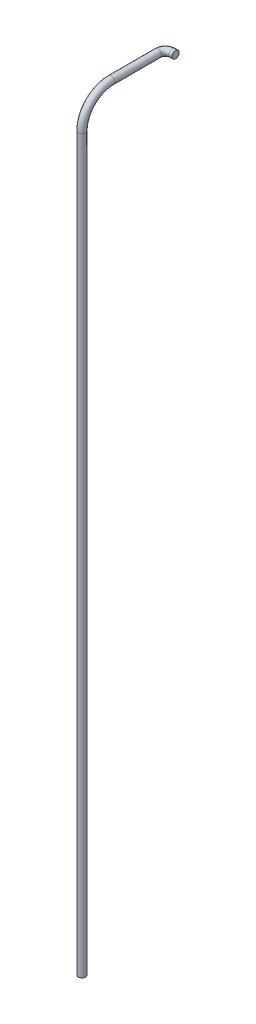
SolidWorks part; units mm, degrees
material "PVC Rígido"
ref_plane "Plano frontal" through (0, 0, 0) normal (0, 0, 1) x (1, 0, 0)
ref_plane "Plano superior" through (0, 0, 0) normal (0, 1, 0) x (1, 0, 0)
ref_plane "Plano direito" through (0, 0, 0) normal (1, 0, 0) x (0, 0, -1)
sketch "Esboço1" plane through (0, 0, 0) normal (1, 0, 0) x (0, 0, -1)
  line L0 (0, 0) -> (-30, 0)
  line L1 (-50, -20) -> (-50, -520)
  arc A1 (-30, 0) -> (-50, -20) centre (-30, -20) ccw
  point P7 (-50, -1505)
  point P10 (-50, 0)
  point P11 (-50, -100)
  dimension "D2" = 20
  dimension "D1" = 50
  dimension "D3" = 500
sweep "Varredura1" add path "Esboço1" circular profile diameter 5 parameters "D3"=5
sketch "Esboço22" plane through (0, 0, 0) normal (0, 1, 0) x (1, 0, 0)
  line L0 (0, 0) -> (0, 2)
  line L1 (5, 7) -> (6.9966, 7)
  arc A0 (0, 2) -> (5, 7) centre (5, 2) cw
  dimension "D1" = 5
  dimension "D2" = 2
sweep "Varredura2" add path "Esboço22" circular profile diameter 5 parameters "D3"=5
ref_plane "Plano1" through (0, -520, 0) normal (0, -1, 0) x (-1, 0, 0)
